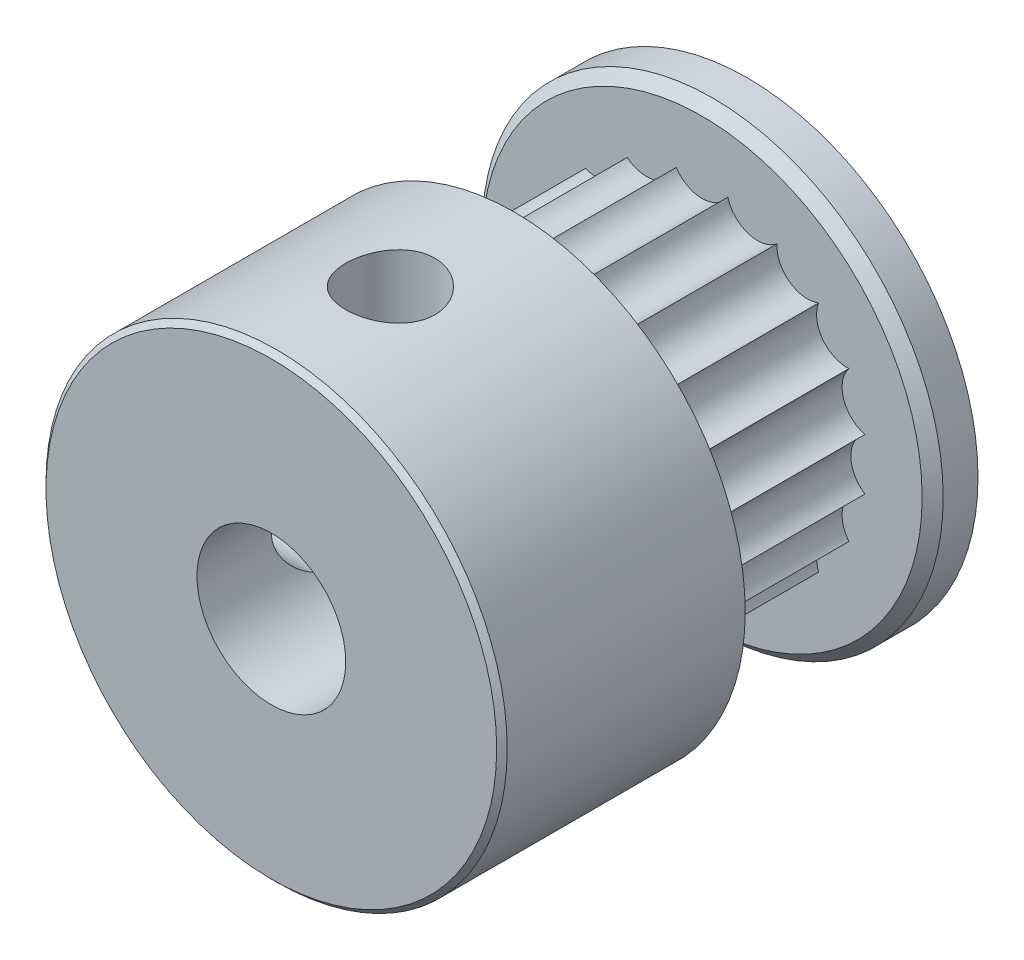
SolidWorks part; units mm, degrees
material "1060 Alloy"
ref_plane "Front Plane" through (0, 0, 0) normal (0, 0, 1) x (1, 0, 0)
ref_plane "Top Plane" through (0, 0, 0) normal (0, 1, 0) x (1, 0, 0)
ref_plane "Right Plane" through (0, 0, 0) normal (1, 0, 0) x (0, 0, -1)
sketch "Sketch1" plane through (0, 0, 0) normal (1, 0, 0) x (0, 0, -1)
  line L0 (-8, 0) -> (8, 0) construction
  line L1 (-7.8232, 7.75) -> (0.1768, 7.75)
  line L2 (0.1768, 7.75) -> (0.1768, 5)
  line L3 (0.1768, 5) -> (6.4768, 5)
  line L4 (6.4768, 5) -> (6.4768, 7.3964)
  line L5 (6.4768, 7.3964) -> (6.8303, 7.75)
  line L6 (6.8303, 7.75) -> (8, 7.75)
  line L7 (8, 7.75) -> (8, 2.5)
  line L8 (-7.8232, 7.75) -> (-8, 7.5732)
  line L9 (-8, 7.5732) -> (-8, 2.5)
  line L10 (8, 2.5) -> (-8, 2.5)
  point P4 (0, 0)
  dimension "D1" = 16
  dimension "D2" = 7.75
  dimension "D3" = 8
  dimension "D4" = 2.5
  dimension "D5" = 6.3
  dimension "D6" = 0.25
  dimension "D7" = 45
  dimension "D8" = 45
  dimension "D9" = 0.5
  dimension "D10" = 5
revolve "Revolve1" add sketch "Sketch1" angle 360 about L0
sketch "Sketch2" plane through (0, 0, 0) normal (0, 1, 0) x (1, 0, 0)
  line L0 (-7.5732, -8) -> (7.5732, -8) construction
  circle A0 centre (0, -4) radius 1.5
  dimension "D2" = 3
  dimension "D1" = 4
extrude "Cut-Extrude1" cut sketch "Sketch2" along normal blind 29
pattern_circular "CirPattern1" count 2 over 90 about axis through (0, 0, 8) along (0, 0, 1) of "Cut-Extrude1"
sketch "Sketch3" plane through (0, 0, -6.4768) normal (0, 0, 1) x (1, 0, 0)
  arc A0 (-0.8666, 5.4716) -> (0.8666, 5.4716) centre (0, 6.0321) ccw
  circle A1 centre (0, 0) radius 5 construction
  arc A2 (0.8666, 5.4716) -> (2.515, 4.936) centre (1.864, 5.7369) ccw
  arc A3 (2.515, 4.936) -> (3.9172, 3.9172) centre (3.5456, 4.8801) ccw
  arc A4 (3.9172, 3.9172) -> (4.936, 2.515) centre (4.8801, 3.5456) ccw
  arc A5 (4.936, 2.515) -> (5.4716, 0.8666) centre (5.7369, 1.864) ccw
  arc A6 (5.4716, 0.8666) -> (5.4716, -0.8666) centre (6.0321, 0) ccw
  arc A7 (5.4716, -0.8666) -> (4.936, -2.515) centre (5.7369, -1.864) ccw
  arc A8 (4.936, -2.515) -> (3.9172, -3.9172) centre (4.8801, -3.5456) ccw
  arc A9 (3.9172, -3.9172) -> (2.515, -4.936) centre (3.5456, -4.8801) ccw
  arc A10 (2.515, -4.936) -> (0.8666, -5.4716) centre (1.864, -5.7369) ccw
  arc A11 (0.8666, -5.4716) -> (-0.8666, -5.4716) centre (0, -6.0321) ccw
  arc A12 (-0.8666, -5.4716) -> (-2.515, -4.936) centre (-1.864, -5.7369) ccw
  arc A13 (-2.515, -4.936) -> (-3.9172, -3.9172) centre (-3.5456, -4.8801) ccw
  arc A14 (-3.9172, -3.9172) -> (-4.936, -2.515) centre (-4.8801, -3.5456) ccw
  arc A15 (-4.936, -2.515) -> (-5.4716, -0.8666) centre (-5.7369, -1.864) ccw
  arc A16 (-5.4716, -0.8666) -> (-5.4716, 0.8666) centre (-6.0321, 0) ccw
  arc A17 (-5.4716, 0.8666) -> (-4.936, 2.515) centre (-5.7369, 1.864) ccw
  arc A18 (-4.936, 2.515) -> (-3.9172, 3.9172) centre (-4.8801, 3.5456) ccw
  arc A19 (-3.9172, 3.9172) -> (-2.515, 4.936) centre (-3.5456, 4.8801) ccw
  arc A20 (-2.515, 4.936) -> (-0.8666, 5.4716) centre (-1.864, 5.7369) ccw
  circle A21 centre (0, 0) radius 5.5398 construction
  circle A22 centre (0, 0) radius 2.5 construction
  circle A23 centre (0, 0) radius 2.5
  dimension "D2" = 20
extrude "Boss-Extrude1" add sketch "Sketch3" along normal up to surface (6.3 mm away) up to face at (7.75, 0, -0.1768)
sketch "Sketch4" plane through (0, 0, -0.1768) normal (0, 0, -1) x (-1, 0, 0)
  circle A0 centre (0, 0) radius 5.55
  dimension "D1" = 11.1
